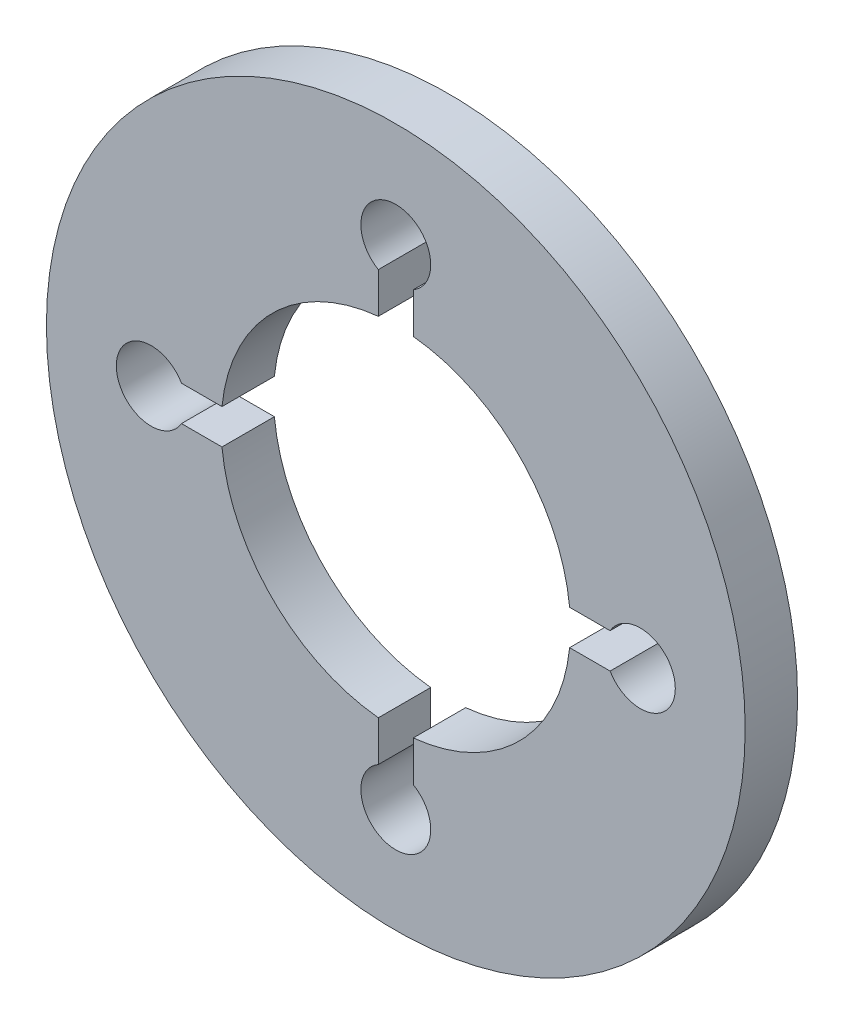
SolidWorks part; units mm, degrees
ref_plane "Plan de face" through (0, 0, 0) normal (0, 0, 1) x (1, 0, 0)
ref_plane "Plan de dessus" through (0, 0, 0) normal (0, 1, 0) x (1, 0, 0)
ref_plane "Plan de droite" through (0, 0, 0) normal (1, 0, 0) x (0, 0, -1)
sketch "Esquisse1" plane through (0, 0, 0) normal (0, 0, 1) x (1, 0, 0)
  line L0 (-0.3193, 0) -> (0, 0) construction
  line L1 (0, 5) -> (0, 0) construction
  line L2 (3.067, 0.25) -> (2.4875, 0.25)
  line L3 (-0.25, 3.067) -> (-0.25, 2.4875)
  line L4 (3.067, -0.25) -> (2.4875, -0.25)
  line L5 (0.25, -3.067) -> (0.25, -2.4875)
  line L6 (0, 9.0177) -> (0, -9.0474) construction
  line L7 (-0.25, -3.067) -> (-0.25, -2.4875)
  line L8 (-3.067, -0.25) -> (-2.4875, -0.25)
  line L9 (-0.25, 9.0177) -> (-0.25, -9.0474) construction
  line L10 (-3.067, 0.25) -> (-2.4875, 0.25)
  line L16 (0.25, 3.067) -> (0.25, 2.4875)
  circle A0 centre (0, 0) radius 5
  arc A1 (2.4875, 0.25) -> (0.25, 2.4875) centre (0, 0) ccw
  arc A2 (3.067, -0.25) -> (3.067, 0.25) centre (3.5, 0) ccw
  arc A3 (-0.25, -3.067) -> (0.25, -3.067) centre (0, -3.5) ccw
  arc A4 (-3.067, 0.25) -> (-3.067, -0.25) centre (-3.5, 0) ccw
  arc A5 (0.25, 3.067) -> (-0.25, 3.067) centre (0, 3.5) ccw
  circle A6 centre (0, 0) radius 3.5 construction
  arc A7 (-2.4875, -0.25) -> (-0.25, -2.4875) centre (0, 0) ccw
  arc A8 (0.25, -2.4875) -> (2.4875, -0.25) centre (0, 0) ccw
  arc A9 (-0.25, 2.4875) -> (-2.4875, 0.25) centre (0, 0) ccw
  dimension "D1" = 10
  dimension "D2" = 5
  dimension "D5" = 1
  dimension "D6" = 7
  dimension "D4" = 0.25
  dimension "D3" = 0.25
  dimension "D7" = 4
extrude "Boss.-Extru.1" add sketch "Esquisse1" along normal blind 0.75
